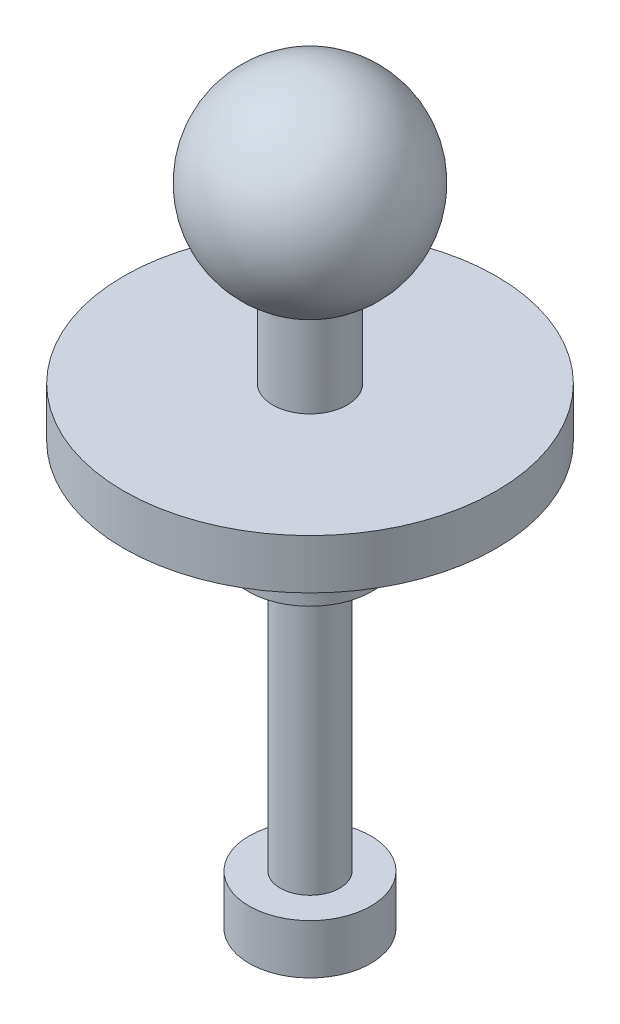
SolidWorks part; units mm, degrees
ref_plane "Front Plane" through (0, 0, 0) normal (0, 0, 1) x (1, 0, 0)
ref_plane "Top Plane" through (0, 0, 0) normal (0, 1, 0) x (1, 0, 0)
ref_plane "Right Plane" through (0, 0, 0) normal (1, 0, 0) x (0, 0, -1)
sketch "Sketch3" plane through (0, 0, 0) normal (0, 1, 0) x (1, 0, 0)
  circle A0 centre (0, 0) radius 7.5
  dimension "D1" = 15
extrude "Boss-Extrude1" add sketch "Sketch3" against normal blind 2 contours A0
sketch "Sketch4" plane through (0, 0, 0) normal (0, 0, 1) x (1, 0, 0)
  line L0 (0, -2) -> (0, -19)
  line L1 (-7.5, -2) -> (7.5, -2) construction
  line L2 (0, -19) -> (-2.45, -19)
  line L3 (-2.45, -19) -> (-2.45, -17)
  line L4 (-2.45, -17) -> (-1.2, -17)
  line L5 (-1.2, -17) -> (-1.2, -6)
  line L6 (-1.2, -6) -> (-2.5, -6)
  line L7 (-2.5, -6) -> (-2.5, -4.5)
  line L8 (-2.5, -4.5) -> (-1.2, -4.5)
  line L9 (-1.2, -4.5) -> (-1.2, -4)
  line L10 (-1.2, -4) -> (-4, -2)
  line L11 (0, -2) -> (-4, -2)
  dimension "D1" = 4
  dimension "D2" = 2
  dimension "D3" = 1.2
  dimension "D4" = 2.5
  dimension "D5" = 1.5
  dimension "D6" = 2
  dimension "D7" = 2.45
  dimension "D8" = 15
  dimension "D9" = 11
revolve "Revolve3" add sketch "Sketch4" angle 360 about L0
sketch "Sketch5" plane through (0, 0, 0) normal (1, 0, 0) x (0, 0, -1)
  line L0 (0, 0) -> (0, 7) construction
  line L1 (7.5, 0) -> (-7.5, 0) construction
  line L2 (-1.5, 3.4) -> (-1.5, 0)
  line L3 (1.5, 3.4) -> (1.5, 0)
  line L4 (0, 0) -> (-1.5, 0)
  line L5 (0, 0) -> (1.5, 0)
  line L6 (0, 10.9) -> (0, 3.1)
  circle A0 centre (0, 7) radius 3.9
  dimension "D2" = 7.8
  dimension "D1" = 7
  dimension "D3" = 3
revolve "Revolve4" add sketch "Sketch5" angle 360 about L6
